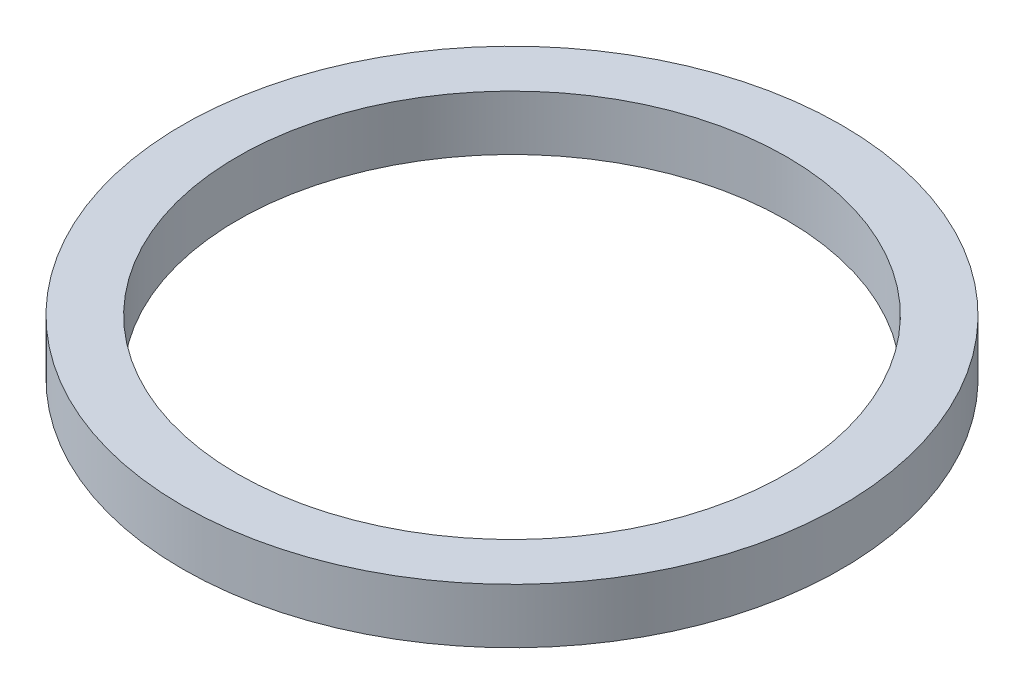
SolidWorks part; units mm, degrees
ref_plane "Front Plane" through (0, 0, 0) normal (0, 0, 1) x (1, 0, 0)
ref_plane "Top Plane" through (0, 0, 0) normal (0, 1, 0) x (1, 0, 0)
ref_plane "Right Plane" through (0, 0, 0) normal (1, 0, 0) x (0, 0, -1)
sketch "Sketch1" plane through (0, 0, 0) normal (0, 1, 0) x (1, 0, 0)
  circle A0 centre (0, 0) radius 30
  circle A1 centre (0, 0) radius 36
extrude "Boss-Extrude1" add sketch "Sketch1" along normal blind 6 contours A1 | A0
